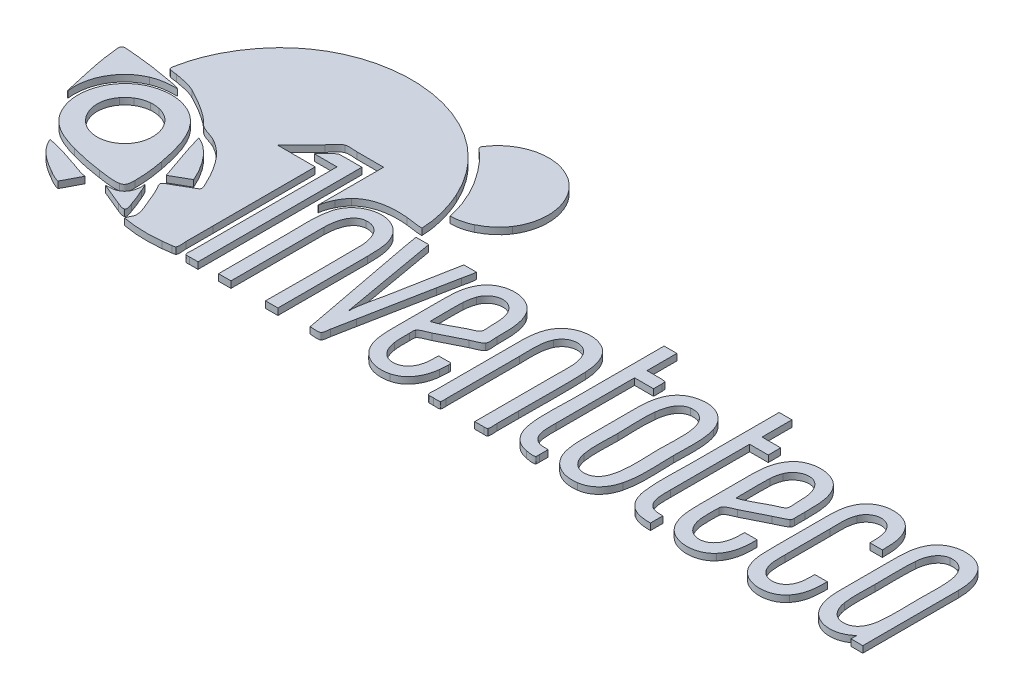
SolidWorks part; units mm, degrees
ref_plane "Alzado" through (0, 0, 0) normal (0, 0, 1) x (1, 0, 0)
ref_plane "Planta" through (0, 0, 0) normal (0, 1, 0) x (1, 0, 0)
ref_plane "Vista lateral" through (0, 0, 0) normal (1, 0, 0) x (0, 0, -1)
sketch "Croquis2" plane through (0, 0, 0) normal (0, 1, 0) x (1, 0, 0)
  line L1 (-10.1434, 10.8277) -> (39.8566, 10.8277)
  line L2 (-10.1434, 10.8277) -> (-10.1434, -4.1723)
  line L3 (-10.1434, -4.1723) -> (39.8566, -4.1723)
  line L4 (39.8566, 10.8277) -> (39.8566, -4.1723)
  line L5 (-10.1434, 10.8277) -> (39.8566, -4.1723) construction
  line L6 (-10.1434, -4.1723) -> (39.8566, 10.8277) construction
  point P0 (14.8566, 3.3277)
  point P5 (16.3009, 1.4154)
  dimension "D1" = 50
  dimension "D2" = 15
sketch "Croquis1" plane through (0, 0, 0) normal (0, 1, 0) x (1, 0, 0)
  line L0 (3.5784, 3.9291) -> (1.8314, 3.9291)
  line L1 (3.9335, 5.4773) -> (5.155, 5.4773)
  line L2 (5.155, 5.4773) -> (5.155, 2.4804)
  line L3 (5.155, 2.4804) -> (5.1692, 2.4804)
  line L4 (3.0387, 4.4262) -> (4.0755, 4.4262)
  line L5 (4.0755, 4.4262) -> (4.0755, -0.829)
  line L6 (4.0755, -0.829) -> (4.0755, -2.0789)
  line L7 (4.2602, -2.5051) -> (4.6579, -2.5051)
  line L8 (4.6579, -2.5051) -> (4.6579, 4.9802)
  line L9 (4.6579, 4.9802) -> (3.9193, 4.9802)
  line L10 (3.9193, 4.9802) -> (3.5926, 4.9716)
  line L11 (3.5926, 4.9716) -> (3.408, 4.8097)
  line L12 (3.408, 4.8097) -> (3.0387, 4.4262)
  line L13 (18.6341, 4.8097) -> (18.6341, 0.7333)
  line L14 (20.0828, -2.3346) -> (20.0828, -1.9369)
  line L15 (19.2164, -0.7154) -> (19.2164, 2.8781)
  line L16 (19.2164, 2.8781) -> (20.0828, 2.8781)
  line L17 (20.0828, 2.8781) -> (20.0828, 3.2758)
  line L18 (20.0828, 3.2758) -> (20.0682, 3.4234)
  line L19 (20.0682, 3.4234) -> (19.8556, 3.4462)
  line L20 (19.8556, 3.4462) -> (19.2164, 3.4462)
  line L21 (19.2164, 3.4462) -> (19.2164, 4.8097)
  line L22 (19.2164, 4.8097) -> (18.6341, 4.8097)
  line L23 (23.8893, 4.8097) -> (23.8893, 0.8044)
  line L24 (25.3239, -2.505) -> (25.3239, -1.9369)
  line L25 (24.4717, -0.7296) -> (24.4717, 2.8781)
  line L26 (24.4717, 2.8781) -> (25.3239, 2.8781)
  line L27 (25.3239, 2.8781) -> (25.3239, 3.4462)
  line L28 (25.3239, 3.4462) -> (24.4717, 3.4462)
  line L29 (24.4717, 3.4462) -> (24.4717, 4.8097)
  line L30 (24.4717, 4.8097) -> (23.8893, 4.8097)
  line L31 (-5.0999, 1.3015) -> (-5.0857, 1.3015)
  line L32 (5.5953, -2.505) -> (6.1634, -2.505)
  line L33 (7.74, -2.505) -> (8.3082, -2.505)
  line L34 (8.3082, -2.505) -> (8.3082, 1.5856)
  line L35 (5.5953, 0.6765) -> (5.5953, -2.505)
  line L36 (12.8249, 0.0267) -> (13.9469, 0.5878)
  line L37 (11.7312, 1.4009) -> (11.7312, -0.3177)
  line L38 (14.2736, -0.7296) -> (13.8759, -0.7296)
  line L39 (17.2989, -2.505) -> (17.725, -2.505)
  line L40 (17.8813, -2.0789) -> (17.8813, -1.0989)
  line L41 (15.1542, 1.2731) -> (15.1542, -0.7864)
  line L42 (15.1542, -0.7864) -> (15.1542, -2.0647)
  line L43 (15.7365, -2.2494) -> (15.7365, -1.525)
  line L44 (15.7365, -1.525) -> (15.7365, 1.1026)
  line L45 (17.2989, 1.1737) -> (17.2989, -0.3035)
  line L46 (17.2989, -0.3035) -> (17.2989, -2.505)
  line L47 (20.4521, 1.2447) -> (20.4521, -0.3319)
  line L48 (28.4202, -0.7296) -> (27.8521, -0.7296)
  line L49 (26.7868, 0.0197) -> (27.8379, 0.5452)
  line L50 (28.4202, 0.989) -> (28.4202, 1.4577)
  line L51 (25.7074, 1.3015) -> (25.7074, -0.6444)
  line L52 (31.687, -0.7864) -> (31.1189, -0.7864)
  line L53 (29.6559, -0.687) -> (29.6559, 1.3583)
  line L54 (31.1189, 1.7276) -> (31.687, 1.7276)
  line L55 (29.0878, 1.6992) -> (29.0878, -0.5876)
  line L56 (34.4851, -2.2352) -> (34.4851, -2.505)
  line L57 (34.4851, -2.505) -> (35.0248, -2.505)
  line L58 (35.0248, -2.505) -> (35.0248, 0.0658)
  line L59 (35.0248, 0.0658) -> (35.0248, 1.8696)
  line L60 (32.312, 1.5288) -> (32.312, -0.4029)
  line L61 (8.6632, 3.4462) -> (8.7709, 2.8213)
  line L62 (8.7709, 2.8213) -> (9.0496, 1.3583)
  line L63 (9.0496, 1.3583) -> (9.7853, -2.505)
  line L64 (10.5409, -1.1415) -> (11.1318, 1.9122)
  line L65 (11.4187, 3.4462) -> (10.8506, 3.4462)
  line L66 (10.041, -0.9853) -> (10.0268, -0.9853)
  line L67 (10.0268, -0.9853) -> (9.2456, 3.4462)
  line L68 (9.2456, 3.4462) -> (8.6632, 3.4462)
  line L69 (-0.2279, 2.4094) -> (-0.0054, 1.685)
  line L70 (-0.0054, 1.685) -> (0.5106, 0.1936)
  line L71 (0.5106, 0.1936) -> (1.306, 0.6481)
  line L72 (-0.4694, -1.5818) -> (-0.4694, -1.596)
  line L73 (-1.7335, -2.5051) -> (-1.3074, -1.6955)
  spline S0 degree 3 poles (8.6064, 5.0654) (8.9077, 5.0656) (9.231, 5.1421) (9.5012, 5.275) knots 0 0 0 0 1 1 1 1
  spline S1 degree 3 poles (9.5012, 5.275) (9.8765, 5.4595) (10.2057, 5.7212) (10.4375, 6.0738) knots 0 0 0 0 1 1 1 1
  spline S2 degree 3 poles (10.4375, 6.0738) (11.1456, 7.1512) (10.8182, 8.6685) (9.6859, 9.3162) knots 0 0 0 0 1 1 1 1
  spline S3 degree 3 poles (9.6859, 9.3162) (9.4504, 9.4509) (9.1882, 9.5508) (8.9189, 9.5924) knots 0 0 0 0 1 1 1 1
  spline S4 degree 3 poles (8.9189, 9.5924) (8.2132, 9.7014) (7.5188, 9.4932) (6.9872, 9.0163) knots 0 0 0 0 1 1 1 1
  spline S5 degree 3 poles (6.9872, 9.0163) (6.8569, 8.8994) (6.7378, 8.7633) (6.642, 8.6163) knots 0 0 0 0 1 1 1 1
  spline S6 degree 3 poles (6.642, 8.6163) (6.6153, 8.5752) (6.5511, 8.5009) (6.5671, 8.4482) knots 0 0 0 0 1 1 1 1
  spline S7 degree 3 poles (6.5671, 8.4482) (6.5982, 8.3461) (6.7844, 8.2366) (6.8594, 8.1618) knots 0 0 0 0 1 1 1 1
  spline S8 degree 3 poles (6.8594, 8.1618) (7.0821, 7.9394) (7.2857, 7.7003) (7.4783, 7.4516) knots 0 0 0 0 1 1 1 1
  spline S9 degree 3 poles (7.4783, 7.4516) (8.0092, 6.7663) (8.4305, 5.9176) (8.6064, 5.0654) knots 0 0 0 0 1 1 1 1
  spline S10 degree 3 poles (1.249, -2.4482) (1.8259, -2.5553) (2.4283, -2.5697) (3.0103, -2.5074) knots 0 0 0 0 1 1 1 1
  spline S11 degree 3 poles (3.0103, -2.5074) (3.1485, -2.4926) (3.2849, -2.4771) (3.4222, -2.4541) knots 0 0 0 0 1 1 1 1
  spline S12 degree 3 poles (3.4222, -2.4541) (3.4634, -2.4472) (3.536, -2.4479) (3.5638, -2.4115) knots 0 0 0 0 1 1 1 1
  spline S13 degree 3 poles (3.5638, -2.4115) (3.6258, -2.3302) (3.5784, -2.0665) (3.5784, -1.9653) knots 0 0 0 0 1 1 1 1
  spline S14 degree 3 poles (3.5784, -1.9653) (3.5784, -1.5582) (3.5826, -1.1506) (3.5785, -0.7438) knots 0 0 0 0 1 1 1 1
  spline S15 degree 3 poles (3.5785, -0.7438) (3.5624, 0.8135) (3.5784, 2.3718) (3.5784, 3.9291) knots 0 0 0 0 1 1 1 1
  spline S16 degree 3 poles (1.8314, 3.9291) (2.196, 4.2937) (2.5619, 4.657) (2.9251, 5.0228) knots 0 0 0 0 1 1 1 1
  spline S17 degree 3 poles (2.9251, 5.0228) (3.0505, 5.1491) (3.2259, 5.4068) (3.3938, 5.4687) knots 0 0 0 0 1 1 1 1
  spline S18 degree 3 poles (3.3938, 5.4687) (3.5397, 5.5225) (3.7781, 5.4773) (3.9335, 5.4773) knots 0 0 0 0 1 1 1 1
  spline S19 degree 3 poles (5.1692, 2.4804) (5.1849, 2.6775) (5.2637, 2.8864) (5.3504, 3.0627) knots 0 0 0 0 1 1 1 1
  spline S20 degree 3 poles (5.3504, 3.0627) (5.4291, 3.2228) (5.5273, 3.3749) (5.6523, 3.503) knots 0 0 0 0 1 1 1 1
  spline S21 degree 3 poles (5.6523, 3.503) (6.1635, 4.0269) (6.9766, 4.092) (7.669, 4.0261) knots 0 0 0 0 1 1 1 1
  spline S22 degree 3 poles (7.669, 4.0261) (7.9276, 4.0015) (8.1757, 3.9433) (8.436, 3.9433) knots 0 0 0 0 1 1 1 1
  spline S23 degree 3 poles (8.436, 3.9433) (8.4211, 4.6648) (8.1948, 5.4069) (7.9006, 6.0596) knots 0 0 0 0 1 1 1 1
  spline S24 degree 3 poles (7.9006, 6.0596) (7.6039, 6.7178) (7.1847, 7.3109) (6.6748, 7.8209) knots 0 0 0 0 1 1 1 1
  spline S25 degree 3 poles (6.6748, 7.8209) (4.3405, 10.1551) (0.3296, 10.1882) (-1.9888, 7.7924) knots 0 0 0 0 1 1 1 1
  spline S26 degree 3 poles (-1.9888, 7.7924) (-2.5824, 7.179) (-3.048, 6.4468) (-3.3469, 5.6477) knots 0 0 0 0 1 1 1 1
  spline S27 degree 3 poles (-3.3469, 5.6477) (-3.4496, 5.373) (-3.5439, 5.0853) (-3.5932, 4.7955) knots 0 0 0 0 1 1 1 1
  spline S28 degree 3 poles (-3.5932, 4.7955) (-3.6044, 4.7295) (-3.6663, 4.5655) (-3.6223, 4.5076) knots 0 0 0 0 1 1 1 1
  spline S29 degree 3 poles (-3.6223, 4.5076) (-3.5662, 4.4338) (-3.3265, 4.4339) (-3.2393, 4.4176) knots 0 0 0 0 1 1 1 1
  spline S30 degree 3 poles (-3.2393, 4.4176) (-2.9214, 4.358) (-2.5794, 4.305) (-2.2876, 4.1591) knots 0 0 0 0 1 1 1 1
  spline S31 degree 3 poles (-2.2876, 4.1591) (-1.8381, 3.9343) (-1.3834, 3.6639) (-0.9809, 3.3625) knots 0 0 0 0 1 1 1 1
  spline S32 degree 3 poles (-0.9809, 3.3625) (-0.8218, 3.2433) (-0.7083, 3.076) (-0.5406, 2.9695) knots 0 0 0 0 1 1 1 1
  spline S33 degree 3 poles (-0.5406, 2.9695) (-0.3336, 2.8379) (-0.0782, 2.7996) (0.1412, 2.6899) knots 0 0 0 0 1 1 1 1
  spline S34 degree 3 poles (0.1412, 2.6899) (0.5113, 2.5048) (0.836, 2.1978) (1.0843, 1.8696) knots 0 0 0 0 1 1 1 1
  spline S35 degree 3 poles (1.0843, 1.8696) (1.33, 1.5449) (1.5407, 1.1895) (1.7079, 0.8186) knots 0 0 0 0 1 1 1 1
  spline S36 degree 3 poles (1.7079, 0.8186) (1.7431, 0.7404) (1.8858, 0.5189) (1.8243, 0.4405) knots 0 0 0 0 1 1 1 1
  spline S37 degree 3 poles (1.8243, 0.4405) (1.7648, 0.3647) (1.63, 0.3142) (1.5473, 0.2668) knots 0 0 0 0 1 1 1 1
  spline S38 degree 3 poles (1.5473, 0.2668) (1.3568, 0.1574) (1.1682, 0.0444) (0.9792, -0.0677) knots 0 0 0 0 1 1 1 1
  spline S39 degree 3 poles (0.9792, -0.0677) (0.9056, -0.1113) (0.7125, -0.1778) (0.7026, -0.2753) knots 0 0 0 0 1 1 1 1
  spline S40 degree 3 poles (0.7026, -0.2753) (0.6938, -0.3635) (0.7928, -0.4849) (0.8328, -0.5592) knots 0 0 0 0 1 1 1 1
  spline S41 degree 3 poles (0.8328, -0.5592) (0.9419, -0.7624) (1.0292, -0.9842) (1.1148, -1.1983) knots 0 0 0 0 1 1 1 1
  spline S42 degree 3 poles (1.1148, -1.1983) (1.2129, -1.4436) (1.3946, -1.782) (1.3874, -2.0505) knots 0 0 0 0 1 1 1 1
  spline S43 degree 3 poles (1.3874, -2.0505) (1.3833, -2.2048) (1.2596, -2.3074) (1.249, -2.4482) knots 0 0 0 0 1 1 1 1
  spline S44 degree 3 poles (4.0755, -2.0789) (4.0755, -2.1593) (4.0324, -2.4382) (4.0983, -2.4904) knots 0 0 0 0 1 1 1 1
  spline S45 degree 3 poles (4.0983, -2.4904) (4.1355, -2.5199) (4.2158, -2.5051) (4.2602, -2.5051) knots 0 0 0 0 1 1 1 1
  spline S46 degree 3 poles (18.6341, 0.7333) (18.6341, 0.0083) (18.5456, -0.7838) (18.6909, -1.4966) knots 0 0 0 0 1 1 1 1
  spline S47 degree 3 poles (18.6909, -1.4966) (18.793, -1.9969) (19.1188, -2.3957) (19.6425, -2.4747) knots 0 0 0 0 1 1 1 1
  spline S48 degree 3 poles (19.6425, -2.4747) (19.7238, -2.487) (20.0105, -2.5551) (20.0682, -2.4823) knots 0 0 0 0 1 1 1 1
  spline S49 degree 3 poles (20.0682, -2.4823) (20.0957, -2.4475) (20.0828, -2.3759) (20.0828, -2.3346) knots 0 0 0 0 1 1 1 1
  spline S50 degree 3 poles (20.0828, -1.9369) (19.9348, -1.9369) (19.7843, -1.944) (19.6425, -1.893) knots 0 0 0 0 1 1 1 1
  spline S51 degree 3 poles (19.6425, -1.893) (19.1744, -1.7245) (19.2164, -1.1155) (19.2164, -0.7154) knots 0 0 0 0 1 1 1 1
  spline S52 degree 3 poles (23.8893, 0.8044) (23.8893, 0.0865) (23.8209, -0.6716) (23.9219, -1.383) knots 0 0 0 0 1 1 1 1
  spline S53 degree 3 poles (23.9219, -1.383) (23.9774, -1.7751) (24.1589, -2.173) (24.5285, -2.3577) knots 0 0 0 0 1 1 1 1
  spline S54 degree 3 poles (24.5285, -2.3577) (24.7735, -2.4803) (25.0542, -2.505) (25.3239, -2.505) knots 0 0 0 0 1 1 1 1
  spline S55 degree 3 poles (25.3239, -1.9369) (25.1804, -1.9369) (25.0351, -1.9424) (24.8978, -1.893) knots 0 0 0 0 1 1 1 1
  spline S56 degree 3 poles (24.8978, -1.893) (24.4304, -1.7248) (24.4717, -1.1296) (24.4717, -0.7296) knots 0 0 0 0 1 1 1 1
  spline S57 degree 3 poles (-5.0857, 1.3015) (-5.2118, 2.2995) (-4.6942, 3.2922) (-3.7506, 3.6958) knots 0 0 0 0 1 1 1 1
  spline S58 degree 3 poles (-3.7506, 3.6958) (-3.393, 3.8487) (-3.0397, 3.8723) (-2.6569, 3.8723) knots 0 0 0 0 1 1 1 1
  spline S59 degree 3 poles (-2.6569, 3.8723) (-2.8408, 3.9708) (-3.1066, 3.9878) (-3.3103, 4.0285) knots 0 0 0 0 1 1 1 1
  spline S60 degree 3 poles (-3.3103, 4.0285) (-3.8355, 4.1336) (-4.3684, 4.2018) (-4.9011, 4.2534) knots 0 0 0 0 1 1 1 1
  spline S61 degree 3 poles (-4.9011, 4.2534) (-5.0712, 4.2699) (-5.2428, 4.2744) (-5.4124, 4.2944) knots 0 0 0 0 1 1 1 1
  spline S62 degree 3 poles (-5.4124, 4.2944) (-5.4785, 4.3021) (-5.5696, 4.3043) (-5.6087, 4.2386) knots 0 0 0 0 1 1 1 1
  spline S63 degree 3 poles (-5.6087, 4.2386) (-5.6475, 4.1732) (-5.6211, 4.0706) (-5.6136, 4.0001) knots 0 0 0 0 1 1 1 1
  spline S64 degree 3 poles (-5.6136, 4.0001) (-5.5938, 3.8152) (-5.5734, 3.6303) (-5.5462, 3.4462) knots 0 0 0 0 1 1 1 1
  spline S65 degree 3 poles (-5.5462, 3.4462) (-5.4383, 2.7175) (-5.2486, 2.0198) (-5.0999, 1.3015) knots 0 0 0 0 1 1 1 1
  spline S66 degree 3 poles (6.1634, -2.505) (6.1634, -1.0898) (6.1467, 0.3266) (6.1635, 1.7418) knots 0 0 0 0 1 1 1 1
  spline S67 degree 3 poles (6.1635, 1.7418) (6.169, 2.2046) (6.2911, 2.9193) (6.8736, 2.962) knots 0 0 0 0 1 1 1 1
  spline S68 degree 3 poles (6.8736, 2.962) (7.5002, 3.0079) (7.7269, 2.3808) (7.7398, 1.8554) knots 0 0 0 0 1 1 1 1
  spline S69 degree 3 poles (7.7398, 1.8554) (7.7754, 0.4039) (7.74, -1.053) (7.74, -2.505) knots 0 0 0 0 1 1 1 1
  spline S70 degree 3 poles (8.3082, 1.5856) (8.3082, 2.1988) (8.2853, 2.9291) (7.7258, 3.3178) knots 0 0 0 0 1 1 1 1
  spline S71 degree 3 poles (7.7258, 3.3178) (6.9874, 3.8309) (5.9192, 3.4358) (5.6931, 2.5798) knots 0 0 0 0 1 1 1 1
  spline S72 degree 3 poles (5.6931, 2.5798) (5.5313, 1.9677) (5.5953, 1.3043) (5.5953, 0.6765) knots 0 0 0 0 1 1 1 1
  spline S73 degree 3 poles (13.8759, -0.7296) (13.8759, -1.0655) (13.8736, -1.4161) (13.6835, -1.7096) knots 0 0 0 0 1 1 1 1
  spline S74 degree 3 poles (13.6835, -1.7096) (13.4417, -2.0828) (12.9078, -2.1527) (12.5989, -1.8232) knots 0 0 0 0 1 1 1 1
  spline S75 degree 3 poles (12.5989, -1.8232) (12.4436, -1.6576) (12.3743, -1.4322) (12.3384, -1.2125) knots 0 0 0 0 1 1 1 1
  spline S76 degree 3 poles (12.3384, -1.2125) (12.3002, -0.9785) (12.3135, -0.7388) (12.3135, -0.5024) knots 0 0 0 0 1 1 1 1
  spline S77 degree 3 poles (12.3135, -0.5024) (12.3135, -0.431) (12.2885, -0.3001) (12.3282, -0.238) knots 0 0 0 0 1 1 1 1
  spline S78 degree 3 poles (12.3282, -0.238) (12.4037, -0.1195) (12.6997, -0.0359) (12.8249, 0.0267) knots 0 0 0 0 1 1 1 1
  spline S79 degree 3 poles (13.9469, 0.5878) (14.0847, 0.6567) (14.3335, 0.7261) (14.4355, 0.8418) knots 0 0 0 0 1 1 1 1
  spline S80 degree 3 poles (14.4355, 0.8418) (14.5115, 0.928) (14.4583, 1.2316) (14.4583, 1.3441) knots 0 0 0 0 1 1 1 1
  spline S81 degree 3 poles (14.4583, 1.3441) (14.4583, 1.8539) (14.4759, 2.3949) (14.2414, 2.8639) knots 0 0 0 0 1 1 1 1
  spline S82 degree 3 poles (14.2414, 2.8639) (13.8167, 3.7132) (12.4813, 3.7693) (11.9932, 2.9491) knots 0 0 0 0 1 1 1 1
  spline S83 degree 3 poles (11.9932, 2.9491) (11.7168, 2.4845) (11.7312, 1.922) (11.7312, 1.4009) knots 0 0 0 0 1 1 1 1
  spline S84 degree 3 poles (11.7312, -0.3177) (11.7312, -0.7614) (11.7137, -1.2075) (11.8367, -1.6386) knots 0 0 0 0 1 1 1 1
  spline S85 degree 3 poles (11.8367, -1.6386) (12.0444, -2.3666) (12.7389, -2.7261) (13.464, -2.5491) knots 0 0 0 0 1 1 1 1
  spline S86 degree 3 poles (13.464, -2.5491) (14.0706, -2.401) (14.363, -1.8326) (14.4321, -1.2551) knots 0 0 0 0 1 1 1 1
  spline S87 degree 3 poles (14.4321, -1.2551) (14.4472, -1.1283) (14.4583, -0.9994) (14.4583, -0.8716) knots 0 0 0 0 1 1 1 1
  spline S88 degree 3 poles (14.4583, -0.8716) (14.4583, -0.8345) (14.4689, -0.7707) (14.4355, -0.7442) knots 0 0 0 0 1 1 1 1
  spline S89 degree 3 poles (14.4355, -0.7442) (14.3983, -0.7148) (14.3179, -0.7296) (14.2736, -0.7296) knots 0 0 0 0 1 1 1 1
  spline S90 degree 3 poles (17.725, -2.505) (17.7682, -2.505) (17.8493, -2.5197) (17.8728, -2.4721) knots 0 0 0 0 1 1 1 1
  spline S91 degree 3 poles (17.8728, -2.4721) (17.9191, -2.3779) (17.8813, -2.1835) (17.8813, -2.0789) knots 0 0 0 0 1 1 1 1
  spline S92 degree 3 poles (17.8813, -1.0989) (17.8813, -0.0732) (17.9125, 0.9594) (17.8676, 1.9833) knots 0 0 0 0 1 1 1 1
  spline S93 degree 3 poles (17.8676, 1.9833) (17.846, 2.4772) (17.7168, 3.0451) (17.2705, 3.3313) knots 0 0 0 0 1 1 1 1
  spline S94 degree 3 poles (17.2705, 3.3313) (16.5801, 3.7741) (15.5934, 3.4929) (15.3023, 2.7218) knots 0 0 0 0 1 1 1 1
  spline S95 degree 3 poles (15.3023, 2.7218) (15.1284, 2.2611) (15.1542, 1.7567) (15.1542, 1.2731) knots 0 0 0 0 1 1 1 1
  spline S96 degree 3 poles (15.1542, -2.0647) (15.1542, -2.1471) (15.1097, -2.4372) (15.1769, -2.4904) knots 0 0 0 0 1 1 1 1
  spline S97 degree 3 poles (15.1769, -2.4904) (15.2274, -2.5303) (15.3627, -2.505) (15.4241, -2.505) knots 0 0 0 0 1 1 1 1
  spline S98 degree 3 poles (15.4241, -2.505) (15.4937, -2.505) (15.6573, -2.5352) (15.7138, -2.4904) knots 0 0 0 0 1 1 1 1
  spline S99 degree 3 poles (15.7138, -2.4904) (15.7625, -2.4518) (15.7365, -2.3053) (15.7365, -2.2494) knots 0 0 0 0 1 1 1 1
  spline S100 degree 3 poles (15.7365, 1.1026) (15.7365, 1.5661) (15.6716, 2.0888) (15.8688, 2.523) knots 0 0 0 0 1 1 1 1
  spline S101 degree 3 poles (15.8688, 2.523) (16.1063, 3.0459) (16.8034, 3.1218) (17.1133, 2.6224) knots 0 0 0 0 1 1 1 1
  spline S102 degree 3 poles (17.1133, 2.6224) (17.3724, 2.2051) (17.2989, 1.6412) (17.2989, 1.1737) knots 0 0 0 0 1 1 1 1
  spline S103 degree 3 poles (21.6736, 3.5254) (21.1756, 3.4592) (20.7933, 3.2202) (20.6056, 2.736) knots 0 0 0 0 1 1 1 1
  spline S104 degree 3 poles (20.6056, 2.736) (20.4224, 2.2629) (20.4521, 1.7424) (20.4521, 1.2447) knots 0 0 0 0 1 1 1 1
  spline S105 degree 3 poles (20.4521, -0.3319) (20.4521, -0.7523) (20.4386, -1.1711) (20.5426, -1.5818) knots 0 0 0 0 1 1 1 1
  spline S106 degree 3 poles (20.5426, -1.5818) (20.7266, -2.3081) (21.3444, -2.6751) (22.0713, -2.572) knots 0 0 0 0 1 1 1 1
  spline S107 degree 3 poles (22.0713, -2.572) (22.632, -2.4925) (22.9742, -2.0485) (23.1029, -1.525) knots 0 0 0 0 1 1 1 1
  spline S108 degree 3 poles (23.1029, -1.525) (23.2759, -0.8203) (23.1792, -0.0161) (23.1792, 0.705) knots 0 0 0 0 1 1 1 1
  spline S109 degree 3 poles (23.1792, 0.705) (23.1792, 1.3385) (23.2571, 2.0402) (23.056, 2.6508) knots 0 0 0 0 1 1 1 1
  spline S110 degree 3 poles (23.056, 2.6508) (22.8601, 3.2453) (22.3012, 3.6088) (21.6736, 3.5254) knots 0 0 0 0 1 1 1 1
  spline S111 degree 3 poles (27.8521, -0.7296) (27.8521, -1.0649) (27.8467, -1.4176) (27.6575, -1.7096) knots 0 0 0 0 1 1 1 1
  spline S112 degree 3 poles (27.6575, -1.7096) (27.395, -2.115) (26.8232, -2.1464) (26.5244, -1.7665) knots 0 0 0 0 1 1 1 1
  spline S113 degree 3 poles (26.5244, -1.7665) (26.2184, -1.3775) (26.2866, -0.7937) (26.2897, -0.3319) knots 0 0 0 0 1 1 1 1
  spline S114 degree 3 poles (26.2897, -0.3319) (26.291, -0.1431) (26.6374, -0.055) (26.7868, 0.0197) knots 0 0 0 0 1 1 1 1
  spline S115 degree 3 poles (27.8379, 0.5452) (28.0134, 0.633) (28.2117, 0.7076) (28.3755, 0.8157) knots 0 0 0 0 1 1 1 1
  spline S116 degree 3 poles (28.3755, 0.8157) (28.4344, 0.8546) (28.4202, 0.9268) (28.4202, 0.989) knots 0 0 0 0 1 1 1 1
  spline S117 degree 3 poles (28.4202, 1.4577) (28.4202, 2.1038) (28.4332, 2.8943) (27.8379, 3.3121) knots 0 0 0 0 1 1 1 1
  spline S118 degree 3 poles (27.8379, 3.3121) (27.4055, 3.6156) (26.7003, 3.6153) (26.2755, 3.2969) knots 0 0 0 0 1 1 1 1
  spline S119 degree 3 poles (26.2755, 3.2969) (26.0635, 3.1379) (25.9265, 2.9118) (25.8383, 2.665) knots 0 0 0 0 1 1 1 1
  spline S120 degree 3 poles (25.8383, 2.665) (25.6821, 2.2279) (25.7074, 1.7578) (25.7074, 1.3015) knots 0 0 0 0 1 1 1 1
  spline S121 degree 3 poles (25.7074, -0.6444) (25.7074, -1.134) (25.7268, -1.6575) (26.0108, -2.0789) knots 0 0 0 0 1 1 1 1
  spline S122 degree 3 poles (26.0108, -2.0789) (26.4425, -2.7199) (27.5261, -2.7746) (28.0326, -2.1926) knots 0 0 0 0 1 1 1 1
  spline S123 degree 3 poles (28.0326, -2.1926) (28.3857, -1.7868) (28.4307, -1.2407) (28.4202, -0.7296) knots 0 0 0 0 1 1 1 1
  spline S124 degree 3 poles (31.1189, -0.7864) (31.1189, -1.0988) (31.1247, -1.4528) (30.9433, -1.7238) knots 0 0 0 0 1 1 1 1
  spline S125 degree 3 poles (30.9433, -1.7238) (30.6722, -2.129) (30.0842, -2.1175) (29.8221, -1.7096) knots 0 0 0 0 1 1 1 1
  spline S126 degree 3 poles (29.8221, -1.7096) (29.6349, -1.4183) (29.6559, -1.0185) (29.6559, -0.687) knots 0 0 0 0 1 1 1 1
  spline S127 degree 3 poles (29.6559, 1.3583) (29.6559, 1.7297) (29.6099, 2.157) (29.7534, 2.5088) knots 0 0 0 0 1 1 1 1
  spline S128 degree 3 poles (29.7534, 2.5088) (29.9487, 2.9872) (30.5759, 3.1426) (30.9125, 2.7076) knots 0 0 0 0 1 1 1 1
  spline S129 degree 3 poles (30.9125, 2.7076) (31.1239, 2.4346) (31.1189, 2.0549) (31.1189, 1.7276) knots 0 0 0 0 1 1 1 1
  spline S130 degree 3 poles (31.687, 1.7276) (31.687, 2.2245) (31.6629, 2.7337) (31.3257, 3.1337) knots 0 0 0 0 1 1 1 1
  spline S131 degree 3 poles (31.3257, 3.1337) (30.8391, 3.7111) (29.7916, 3.6561) (29.3683, 3.0343) knots 0 0 0 0 1 1 1 1
  spline S132 degree 3 poles (29.3683, 3.0343) (29.0996, 2.6396) (29.0878, 2.1582) (29.0878, 1.6992) knots 0 0 0 0 1 1 1 1
  spline S133 degree 3 poles (29.0878, -0.5876) (29.0878, -1.0915) (29.0672, -1.6212) (29.3497, -2.0647) knots 0 0 0 0 1 1 1 1
  spline S134 degree 3 poles (29.3497, -2.0647) (29.7671, -2.7203) (30.8463, -2.7798) (31.3396, -2.1784) knots 0 0 0 0 1 1 1 1
  spline S135 degree 3 poles (31.3396, -2.1784) (31.6657, -1.7805) (31.687, -1.2751) (31.687, -0.7864) knots 0 0 0 0 1 1 1 1
  spline S136 degree 3 poles (35.0248, 1.8696) (35.0248, 2.3295) (34.9257, 2.8674) (34.5821, 3.2007) knots 0 0 0 0 1 1 1 1
  spline S137 degree 3 poles (34.5821, 3.2007) (34.04, 3.7265) (32.9734, 3.6293) (32.5763, 2.9775) knots 0 0 0 0 1 1 1 1
  spline S138 degree 3 poles (32.5763, 2.9775) (32.3087, 2.5382) (32.312, 2.025) (32.312, 1.5288) knots 0 0 0 0 1 1 1 1
  spline S139 degree 3 poles (32.312, -0.4029) (32.312, -0.8505) (32.2849, -1.3096) (32.4405, -1.738) knots 0 0 0 0 1 1 1 1
  spline S140 degree 3 poles (32.4405, -1.738) (32.5287, -1.9806) (32.67, -2.209) (32.8801, -2.3641) knots 0 0 0 0 1 1 1 1
  spline S141 degree 3 poles (32.8801, -2.3641) (33.3618, -2.7195) (34.0705, -2.6495) (34.4851, -2.2352) knots 0 0 0 0 1 1 1 1
  spline S142 degree 3 poles (-2.7989, 3.4828) (-3.1486, 3.4363) (-3.4873, 3.3276) (-3.779, 3.1235) knots 0 0 0 0 1 1 1 1
  spline S143 degree 3 poles (-3.779, 3.1235) (-4.7667, 2.4324) (-4.984, 1.0203) (-4.2493, 0.0658) knots 0 0 0 0 1 1 1 1
  spline S144 degree 3 poles (-4.2493, 0.0658) (-3.8559, -0.4453) (-3.2576, -0.6681) (-2.6569, -0.8351) knots 0 0 0 0 1 1 1 1
  spline S145 degree 3 poles (-2.6569, -0.8351) (-2.186, -0.966) (-1.7081, -1.0714) (-1.2224, -1.1295) knots 0 0 0 0 1 1 1 1
  spline S146 degree 3 poles (-1.2224, -1.1295) (-0.9209, -1.1656) (-0.5431, -1.2464) (-0.2423, -1.1936) knots 0 0 0 0 1 1 1 1
  spline S147 degree 3 poles (-0.2423, -1.1936) (0.0019, -1.1508) (-0.0009, -0.9264) (-0.0009, -0.7296) knots 0 0 0 0 1 1 1 1
  spline S148 degree 3 poles (-0.0009, -0.7296) (-0.0009, -0.2796) (-0.0544, 0.1771) (-0.1374, 0.6197) knots 0 0 0 0 1 1 1 1
  spline S149 degree 3 poles (-0.1374, 0.6197) (-0.3277, 1.6352) (-0.6234, 2.7969) (-1.6343, 3.2863) knots 0 0 0 0 1 1 1 1
  spline S150 degree 3 poles (-1.6343, 3.2863) (-1.8009, 3.367) (-1.9786, 3.4216) (-2.1598, 3.4576) knots 0 0 0 0 1 1 1 1
  spline S151 degree 3 poles (-2.1598, 3.4576) (-2.3616, 3.4976) (-2.5944, 3.51) (-2.7989, 3.4828) knots 0 0 0 0 1 1 1 1
  spline S152 degree 3 poles (9.7853, -2.505) (9.8924, -2.505) (10.1743, -2.5557) (10.2599, -2.4904) knots 0 0 0 0 1 1 1 1
  spline S153 degree 3 poles (10.2599, -2.4904) (10.3266, -2.4396) (10.3317, -2.2158) (10.3478, -2.1357) knots 0 0 0 0 1 1 1 1
  spline S154 degree 3 poles (10.3478, -2.1357) (10.4138, -1.8047) (10.477, -1.473) (10.5409, -1.1415) knots 0 0 0 0 1 1 1 1
  spline S155 degree 3 poles (11.1318, 1.9122) (11.194, 2.2342) (11.2559, 2.5563) (11.3193, 2.8781) knots 0 0 0 0 1 1 1 1
  spline S156 degree 3 poles (11.3193, 2.8781) (11.3558, 3.0635) (11.4147, 3.2567) (11.4187, 3.4462) knots 0 0 0 0 1 1 1 1
  spline S157 degree 3 poles (10.8506, 3.4462) (10.658, 2.4534) (10.4702, 1.4588) (10.2907, 0.4635) knots 0 0 0 0 1 1 1 1
  spline S158 degree 3 poles (10.2907, 0.4635) (10.2062, -0.0049) (10.0423, -0.5084) (10.041, -0.9853) knots 0 0 0 0 1 1 1 1
  spline S159 degree 3 poles (12.3135, 0.4351) (12.3135, 0.9401) (12.2919, 1.4504) (12.3142, 1.9548) knots 0 0 0 0 1 1 1 1
  spline S160 degree 3 poles (12.3142, 1.9548) (12.3217, 2.1278) (12.3608, 2.3033) (12.4179, 2.4662) knots 0 0 0 0 1 1 1 1
  spline S161 degree 3 poles (12.4179, 2.4662) (12.5939, 2.9676) (13.2485, 3.1556) (13.6178, 2.736) knots 0 0 0 0 1 1 1 1
  spline S162 degree 3 poles (13.6178, 2.736) (13.8624, 2.4581) (13.876, 2.0347) (13.876, 1.685) knots 0 0 0 0 1 1 1 1
  spline S163 degree 3 poles (13.876, 1.685) (13.876, 1.5734) (13.9257, 1.3033) (13.8614, 1.2111) knots 0 0 0 0 1 1 1 1
  spline S164 degree 3 poles (13.8614, 1.2111) (13.7922, 1.112) (13.5574, 1.0463) (13.4499, 0.9925) knots 0 0 0 0 1 1 1 1
  spline S165 degree 3 poles (13.4499, 0.9925) (13.0887, 0.8119) (12.7012, 0.5467) (12.3135, 0.4351) knots 0 0 0 0 1 1 1 1
  spline S166 degree 3 poles (21.7021, 2.9592) (22.1935, 3.0232) (22.4782, 2.6546) (22.562, 2.2105) knots 0 0 0 0 1 1 1 1
  spline S167 degree 3 poles (22.562, 2.2105) (22.6598, 1.6913) (22.5969, 1.1183) (22.5969, 0.5913) knots 0 0 0 0 1 1 1 1
  spline S168 degree 3 poles (22.5969, 0.5913) (22.5969, 0.0555) (22.6608, -0.5254) (22.591, -1.0563) knots 0 0 0 0 1 1 1 1
  spline S169 degree 3 poles (22.591, -1.0563) (22.5357, -1.4759) (22.4111, -1.9678) (21.9152, -2.0322) knots 0 0 0 0 1 1 1 1
  spline S170 degree 3 poles (21.9152, -2.0322) (21.4322, -2.095) (21.1509, -1.7154) (21.0695, -1.2835) knots 0 0 0 0 1 1 1 1
  spline S171 degree 3 poles (21.0695, -1.2835) (20.974, -0.7776) (21.0345, -0.2205) (21.0345, 0.293) knots 0 0 0 0 1 1 1 1
  spline S172 degree 3 poles (21.0345, 0.293) (21.0345, 0.8494) (20.9732, 1.4453) (21.0387, 1.9975) knots 0 0 0 0 1 1 1 1
  spline S173 degree 3 poles (21.0387, 1.9975) (21.0868, 2.4044) (21.2242, 2.8969) (21.7021, 2.9592) knots 0 0 0 0 1 1 1 1
  spline S174 degree 3 poles (26.2898, 0.4351) (26.2898, 0.9495) (26.268, 1.4693) (26.2905, 1.9833) knots 0 0 0 0 1 1 1 1
  spline S175 degree 3 poles (26.2905, 1.9833) (26.2977, 2.1479) (26.3339, 2.3277) (26.3957, 2.4804) knots 0 0 0 0 1 1 1 1
  spline S176 degree 3 poles (26.3957, 2.4804) (26.5848, 2.947) (27.2097, 3.1662) (27.5799, 2.7502) knots 0 0 0 0 1 1 1 1
  spline S177 degree 3 poles (27.5799, 2.7502) (27.8277, 2.4716) (27.8523, 2.0525) (27.8523, 1.6992) knots 0 0 0 0 1 1 1 1
  spline S178 degree 3 poles (27.8523, 1.6992) (27.8523, 1.5847) (27.9037, 1.3056) (27.8377, 1.2111) knots 0 0 0 0 1 1 1 1
  spline S179 degree 3 poles (27.8377, 1.2111) (27.7685, 1.112) (27.5337, 1.0463) (27.4262, 0.9925) knots 0 0 0 0 1 1 1 1
  spline S180 degree 3 poles (27.4262, 0.9925) (27.065, 0.8119) (26.6775, 0.5467) (26.2898, 0.4351) knots 0 0 0 0 1 1 1 1
  spline S181 degree 3 poles (33.5479, 2.9592) (34.0622, 3.0262) (34.3477, 2.6316) (34.4222, 2.1679) knots 0 0 0 0 1 1 1 1
  spline S182 degree 3 poles (34.4222, 2.1679) (34.5004, 1.6824) (34.4569, 1.1672) (34.4569, 0.6765) knots 0 0 0 0 1 1 1 1
  spline S183 degree 3 poles (34.4569, 0.6765) (34.4569, 0.0893) (34.496, -0.5144) (34.4403, -1.0989) knots 0 0 0 0 1 1 1 1
  spline S184 degree 3 poles (34.4403, -1.0989) (34.4014, -1.5073) (34.2403, -1.9718) (33.7751, -2.0322) knots 0 0 0 0 1 1 1 1
  spline S185 degree 3 poles (33.7751, -2.0322) (33.2618, -2.0989) (32.9768, -1.687) (32.9106, -1.2267) knots 0 0 0 0 1 1 1 1
  spline S186 degree 3 poles (32.9106, -1.2267) (32.8431, -0.7573) (32.8803, -0.2658) (32.8803, 0.2078) knots 0 0 0 0 1 1 1 1
  spline S187 degree 3 poles (32.8803, 0.2078) (32.8803, 0.8165) (32.853, 1.4333) (32.8958, 2.0401) knots 0 0 0 0 1 1 1 1
  spline S188 degree 3 poles (32.8958, 2.0401) (32.9234, 2.4312) (33.109, 2.902) (33.5479, 2.9592) knots 0 0 0 0 1 1 1 1
  spline S189 degree 3 poles (-2.7277, 2.7036) (-2.5814, 2.7211) (-2.43, 2.7037) (-2.2874, 2.6699) knots 0 0 0 0 1 1 1 1
  spline S190 degree 3 poles (-2.2874, 2.6699) (-1.1935, 2.4111) (-0.9731, 0.8855) (-1.9323, 0.3137) knots 0 0 0 0 1 1 1 1
  spline S191 degree 3 poles (-1.9323, 0.3137) (-2.0844, 0.223) (-2.2536, 0.1625) (-2.4295, 0.1409) knots 0 0 0 0 1 1 1 1
  spline S192 degree 3 poles (-2.4295, 0.1409) (-3.5335, 0.0052) (-4.3235, 1.2936) (-3.6334, 2.1963) knots 0 0 0 0 1 1 1 1
  spline S193 degree 3 poles (-3.6334, 2.1963) (-3.5368, 2.3227) (-3.4182, 2.4341) (-3.2817, 2.5166) knots 0 0 0 0 1 1 1 1
  spline S194 degree 3 poles (-3.2817, 2.5166) (-3.1119, 2.6193) (-2.9245, 2.68) (-2.7277, 2.7036) knots 0 0 0 0 1 1 1 1
  spline S195 degree 3 poles (1.306, 0.6481) (1.0971, 1.15) (0.7734, 1.6633) (0.3686, 2.0283) knots 0 0 0 0 1 1 1 1
  spline S196 degree 3 poles (0.3686, 2.0283) (0.1962, 2.1837) (-0.0003, 2.3438) (-0.2279, 2.4094) knots 0 0 0 0 1 1 1 1
  spline S197 degree 3 poles (0.3828, -0.6586) (0.4278, -1.0147) (0.3325, -1.4031) (-0.0433, -1.5379) knots 0 0 0 0 1 1 1 1
  spline S198 degree 3 poles (-0.0433, -1.5379) (-0.1819, -1.5877) (-0.3247, -1.5818) (-0.4694, -1.5818) knots 0 0 0 0 1 1 1 1
  spline S199 degree 3 poles (-0.4694, -1.596) (-0.137, -1.7344) (0.1856, -1.8843) (0.5248, -2.0072) knots 0 0 0 0 1 1 1 1
  spline S200 degree 3 poles (0.5248, -2.0072) (0.6051, -2.0362) (0.8098, -2.1351) (0.8896, -2.0881) knots 0 0 0 0 1 1 1 1
  spline S201 degree 3 poles (0.8896, -2.0881) (0.9846, -2.0321) (0.8664, -1.797) (0.8421, -1.7239) knots 0 0 0 0 1 1 1 1
  spline S202 degree 3 poles (0.8421, -1.7239) (0.7551, -1.4631) (0.6526, -1.2057) (0.5359, -0.9569) knots 0 0 0 0 1 1 1 1
  spline S203 degree 3 poles (0.5359, -0.9569) (0.4895, -0.8579) (0.453, -0.7434) (0.3828, -0.6586) knots 0 0 0 0 1 1 1 1
  spline S204 degree 3 poles (-3.5657, -1.0421) (-3.3363, -1.5931) (-2.8179, -1.9576) (-2.3158, -2.2412) knots 0 0 0 0 1 1 1 1
  spline S205 degree 3 poles (-2.3158, -2.2412) (-2.1437, -2.3385) (-1.9309, -2.4755) (-1.7335, -2.5051) knots 0 0 0 0 1 1 1 1
  spline S206 degree 3 poles (-1.3074, -1.6955) (-1.5281, -1.6858) (-1.7654, -1.5685) (-1.975, -1.5015) knots 0 0 0 0 1 1 1 1
  spline S207 degree 3 poles (-1.975, -1.5015) (-2.4848, -1.3386) (-3.0358, -1.1201) (-3.5657, -1.0421) knots 0 0 0 0 1 1 1 1
extrude "Saliente-Extruir1" add sketch "Croquis1" along normal blind 0.3
